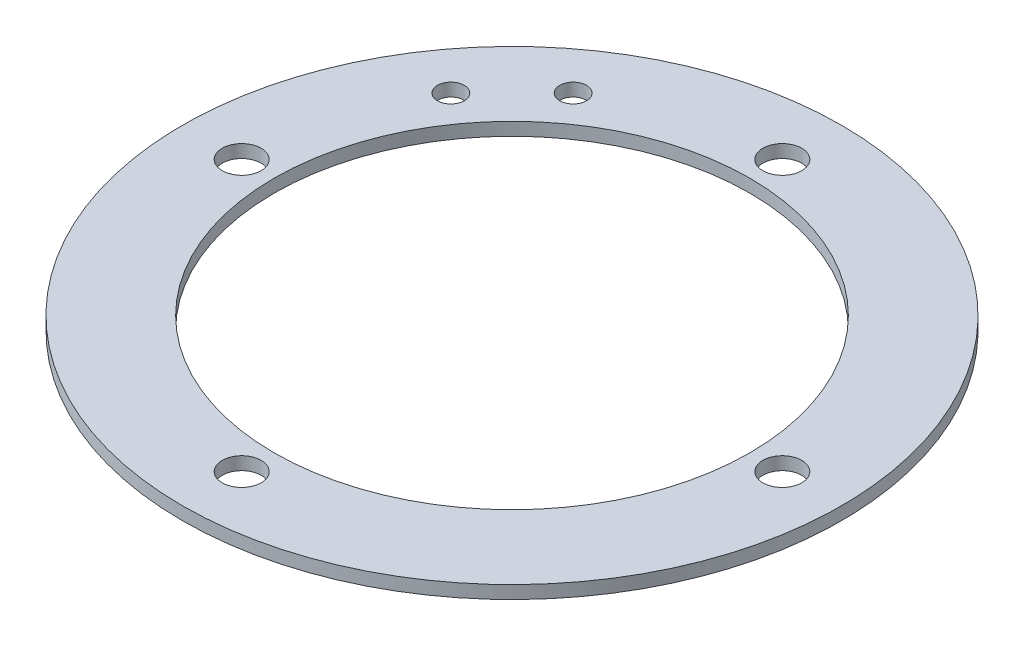
SolidWorks part; units mm, degrees
ref_plane "Front Plane" through (0, 0, 0) normal (0, 0, 1) x (1, 0, 0)
ref_plane "Top Plane" through (0, 0, 0) normal (0, 1, 0) x (1, 0, 0)
ref_plane "Right Plane" through (0, 0, 0) normal (1, 0, 0) x (0, 0, -1)
sketch "Sketch1" plane through (0, 0, 0) normal (0, 1, 0) x (1, 0, 0)
  line L0 (0, 76.2) -> (0, 62.5) construction
  line L1 (0, 62.5) -> (0, 55) construction
  circle A0 centre (0, 0) radius 76.2
  circle A1 centre (0, 0) radius 62.5 construction
  circle A2 centre (0, 62.5) radius 4.5
  circle A3 centre (62.5, 0) radius 4.5
  circle A4 centre (0, -62.5) radius 4.5
  circle A5 centre (-62.5, 0) radius 4.5
  circle A6 centre (0, 0) radius 55
  point P15 (0, 0)
  dimension "D1" = 152.4
  dimension "D2" = 125
  dimension "D3" = 9
  dimension "D5" = 7.5
  dimension "D4" = 4
extrude "Boss-Extrude1" add sketch "Sketch1" along normal blind 3 contours A0
sketch "Sketch2" plane through (0, 3, 0) normal (0, 1, 0) x (1, 0, 0)
  line L0 (-51.6188, 37.4767) -> (-37.4767, 51.6188) construction
  line L1 (-44.5477, 44.5477) -> (0, 0) construction
  line L2 (-76.2, 0) -> (0, 0) construction
  circle A0 centre (-51.6188, 37.4767) radius 3.1
  circle A1 centre (-37.4767, 51.6188) radius 3.1
  circle A2 centre (0, 0) radius 76.2 construction
  point P8 (-79.95, 0)
  point P11 (-39.9904, 54.1326)
  point P12 (-47.3762, 47.3762)
  dimension "D3" = 6.2
  dimension "D1" = 20
  dimension "D2" = 45
  dimension "D4" = 63
extrude "Cut-Extrude1" cut sketch "Sketch2" against normal blind 3 contours A1
